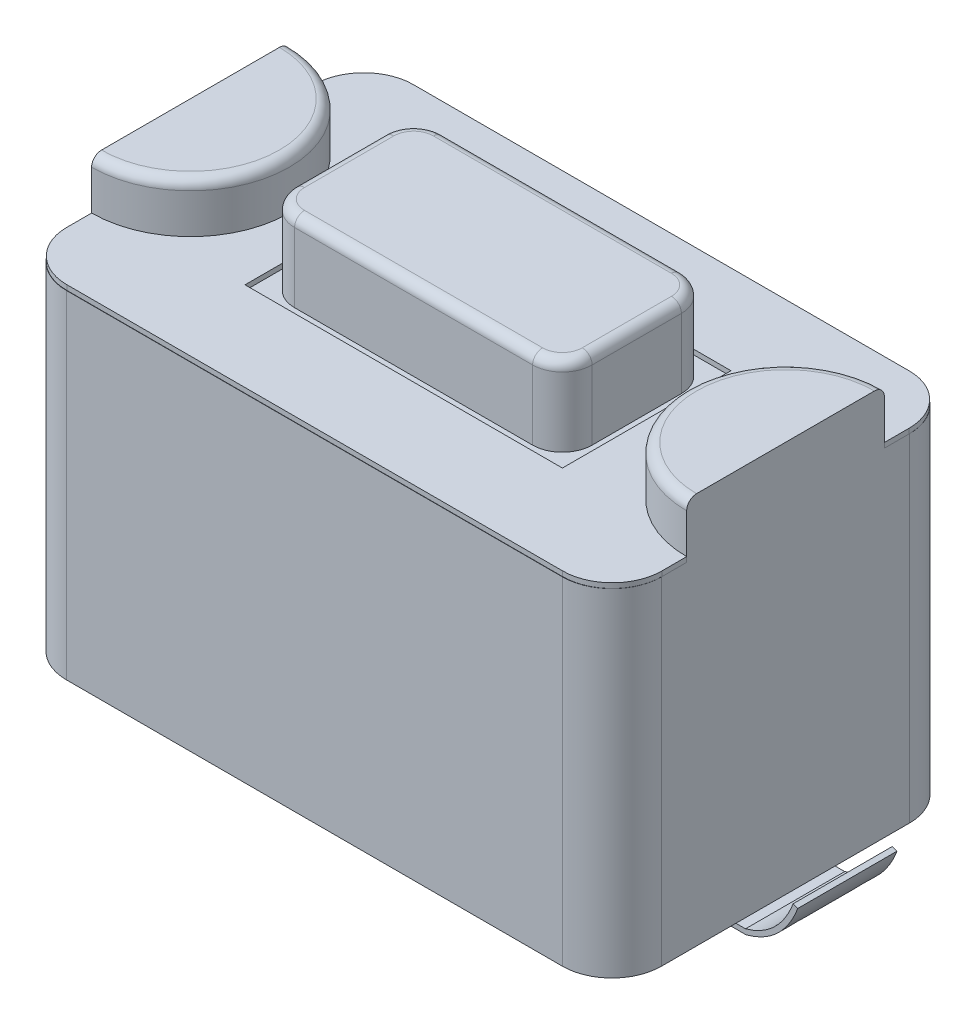
SolidWorks part; units mm, degrees
ref_plane "Спереди" through (0, 0, 0) normal (0, 0, 1) x (1, 0, 0)
ref_plane "Сверху" through (0, 0, 0) normal (0, 1, 0) x (1, 0, 0)
ref_plane "Справа" through (0, 0, 0) normal (1, 0, 0) x (0, 0, -1)
sketch "Эскиз1" plane through (0, 0, 0) normal (0, 1, 0) x (1, 0, 0)
  line L0 (-2.75, 0) -> (2.75, 0) construction
  line L2 (-1.5, -0.75) -> (-4, -0.75)
  line L3 (-1.5, -0.75) -> (-1.5, 0.75)
  line L4 (-1.5, 0.75) -> (-4, 0.75)
  line L5 (-4, -0.75) -> (-4, 0.75)
  line L6 (-1.5, -0.75) -> (-4, 0.75) construction
  line L7 (-1.5, 0.75) -> (-4, -0.75) construction
  line L8 (1.5, 0.75) -> (4, 0.75)
  line L9 (1.5, 0.75) -> (1.5, -0.75)
  line L10 (1.5, -0.75) -> (4, -0.75)
  line L11 (4, 0.75) -> (4, -0.75)
  line L12 (1.5, 0.75) -> (4, -0.75) construction
  line L13 (1.5, -0.75) -> (4, 0.75) construction
sketch "Эскиз3" plane through (0, 0, 0) normal (1, 0, 0) x (0, 0, -1)
  line L0 (0, 0) -> (0, 5) construction
ref_plane "Плоскость1" through (0, 0, 0) normal (0, 0, 1) x (1, 0, 0)
sketch "Эскиз5" plane through (0, 0, 0) normal (0, 0, 1) x (1, 0, 0)
  line L0 (0, 0) -> (0, 5) construction
  line L1 (1.5, 0.025) -> (3.1, 0.025)
  line L2 (3.1, 0) -> (3.6, 0) construction
  line L3 (1.5, 0) -> (4, 0) construction
  line L4 (1.5, 0) -> (4, 0) construction
  line L5 (3.6, 0) -> (3.6, 0.5) construction
  spline S0 degree 2 poles (3.1, 0.025) (3.4555, 0.1224) (3.6, 0.5) knots 0 0 0 1 1 1
  point P0 (0, 0.025)
ref_plane "Плоскость2" through (1.5, 0, 0) normal (-1, 0, 0) x (0, 0, 1)
sketch "Эскиз6" plane through (1.5, 0, 0) normal (-1, 0, 0) x (0, 0, 1)
  line L1 (-0.5, 0) -> (0.5, 0)
  line L2 (-0.5, 0) -> (-0.5, 0.05)
  line L3 (-0.5, 0.05) -> (0.5, 0.05)
  line L4 (0.5, 0) -> (0.5, 0.05)
  line L5 (-0.5, 0) -> (0.5, 0.05) construction
  line L6 (-0.5, 0.05) -> (0.5, 0) construction
  point P0 (0, 0.025)
ref_plane "Плоскость3" through (0, 0, 0) normal (1, 0, 0) x (0, 0, -1)
sketch "Эскиз7" plane through (0, 0, 0) normal (0, 0, 1) x (1, 0, 0)
  line L0 (-1.5, 0.025) -> (-3.1, 0.025)
  line L2 (-3.1, 0.025) -> (-3.6, 0.025) construction
  line L3 (-3.6, 0.025) -> (-3.6, 0.525) construction
  spline S0 degree 2 poles (-3.1, 0.025) (-3.4669, 0.1244) (-3.6, 0.525) knots 0 0 0 1 1 1
  point P0 (-1.5, 0.025)
ref_plane "Плоскость4" through (-1.5, 0, 0) normal (1, 0, 0) x (0, 0, -1)
sketch "Эскиз8" plane through (-1.5, 0, 0) normal (1, 0, 0) x (0, 0, -1)
  line L1 (0.5, 0) -> (-0.5, 0)
  line L2 (0.5, 0) -> (0.5, 0.05)
  line L3 (0.5, 0.05) -> (-0.5, 0.05)
  line L4 (-0.5, 0) -> (-0.5, 0.05)
  line L5 (0.5, 0) -> (-0.5, 0.05) construction
  line L6 (0.5, 0.05) -> (-0.5, 0) construction
  point P0 (0, 0.025)
sweep "По траектории2" add profiles "Эскиз6" path "Эскиз5"
sweep "По траектории3" add profiles "Эскиз8" path "Эскиз7"
sketch "Эскиз9" plane through (0, 0.05, 0) normal (0, 1, 0) x (1, 0, 0)
  line L1 (-2.5, 1.75) -> (2.5, 1.75)
  line L2 (-3, 1.25) -> (-3, -1.25)
  line L3 (-2.5, -1.75) -> (2.5, -1.75)
  line L4 (3, 1.25) -> (3, -1.25)
  line L5 (-3, 1.75) -> (3, -1.75) construction
  line L6 (-3, -1.75) -> (3, 1.75) construction
  arc A0 (-2.5, 1.75) -> (-3, 1.25) centre (-2.5, 1.25) ccw
  arc A1 (2.5, 1.75) -> (3, 1.25) centre (2.5, 1.25) cw
  arc A2 (2.5, -1.75) -> (3, -1.25) centre (2.5, -1.25) ccw
  arc A3 (-3, -1.25) -> (-2.5, -1.75) centre (-2.5, -1.25) ccw
  point P0 (0, 0)
  dimension "D1" = 0.5
extrude "Бобышка-Вытянуть1" add sketch "Эскиз9" along normal blind 3.4
sketch "Эскиз10" plane through (0, 3.45, 0) normal (0, 1, 0) x (1, 0, 0)
  line L0 (-3, 1.25) -> (-3, -1.25) construction
  line L1 (3, -1.25) -> (3, 1.25) construction
  line L2 (-3, 0.9969) -> (-3, -0.9969)
  line L3 (3, 0.9969) -> (3, -0.9969)
  arc A0 (-3, -0.9969) -> (-3, 0.9969) centre (-3, 0) ccw
  arc A1 (3, 0.9969) -> (3, -0.9969) centre (3, 0) ccw
extrude "Бобышка-Вытянуть2" add sketch "Эскиз10" along normal blind 0.55
sketch "Эскиз11" plane through (0, 3.45, 0) normal (0, 1, 0) x (1, 0, 0)
  line L0 (-3, 0.9969) -> (-3, 1.2469)
  line L1 (-2.5, 1.7469) -> (2.5, 1.7469)
  line L2 (3, 1.2469) -> (3, 0.9969)
  line L3 (-3, -0.9969) -> (-3, -1.2469)
  line L4 (-2.5, -1.7469) -> (2.5, -1.7469)
  line L5 (3, -1.2469) -> (3, -0.9969)
  line L7 (-1.6, 0.85) -> (1.6, 0.85)
  line L8 (-1.6, 0.85) -> (-1.6, -0.85)
  line L9 (-1.6, -0.85) -> (1.6, -0.85)
  line L10 (1.6, 0.85) -> (1.6, -0.85)
  line L11 (-1.6, 0.85) -> (1.6, -0.85) construction
  line L12 (-1.6, -0.85) -> (1.6, 0.85) construction
  arc A0 (3, 0.9969) -> (3, -0.9969) centre (3, 0) ccw
  arc A1 (3, 0.9969) -> (3, -0.9969) centre (3, 0) ccw construction
  arc A2 (-3, 0.9969) -> (-3, -0.9969) centre (-3, 0) cw
  arc A3 (-3, 1.2469) -> (-2.5, 1.7469) centre (-2.5, 1.2469) cw
  arc A4 (2.5, 1.7469) -> (3, 1.2469) centre (2.5, 1.2469) cw
  arc A5 (2.5, -1.7469) -> (3, -1.2469) centre (2.5, -1.2469) ccw
  arc A6 (-3, -1.2469) -> (-2.5, -1.7469) centre (-2.5, -1.2469) ccw
  point P24 (0, 0)
  dimension "D1" = 0.5
  dimension "D2" = 0.5
extrude "Бобышка-Вытянуть4" add sketch "Эскиз11" along normal blind 0.05 separate body
sketch "Эскиз12" plane through (0, 3.45, 0) normal (0, 1, 0) x (1, 0, 0)
  line L1 (-1.2, 0.75) -> (1.2, 0.75)
  line L2 (-1.5, 0.45) -> (-1.5, -0.45)
  line L3 (-1.2, -0.75) -> (1.2, -0.75)
  line L4 (1.5, 0.45) -> (1.5, -0.45)
  line L5 (-1.5, 0.75) -> (1.5, -0.75) construction
  line L6 (-1.5, -0.75) -> (1.5, 0.75) construction
  arc A0 (1.2, 0.75) -> (1.5, 0.45) centre (1.2, 0.45) cw
  arc A1 (1.2, -0.75) -> (1.5, -0.45) centre (1.2, -0.45) ccw
  arc A2 (-1.5, -0.45) -> (-1.2, -0.75) centre (-1.2, -0.45) ccw
  arc A3 (-1.2, 0.75) -> (-1.5, 0.45) centre (-1.2, 0.45) ccw
  point P0 (0, 0)
  dimension "D1" = 0.3
extrude "Бобышка-Вытянуть5" add sketch "Эскиз12" along normal blind 0.8 separate body
fillet "Скругление1" radius 0.1 8 edges at (1.5, 4.25, 0) (1.4121, 4.25, 0.6621) (0, 4.25, 0.75) (-1.4121, 4.25, 0.6621) (-1.5, 4.25, 0) (-1.4121, 4.25, -0.6621) (0, 4.25, -0.75) (1.4121, 4.25, -0.6621)
fillet "Скругление2" radius 0.1 1 edges at (2.0031, 4, 0)
fillet "Скругление3" radius 0.1 3 edges at (-2.0031, 4, 0)
